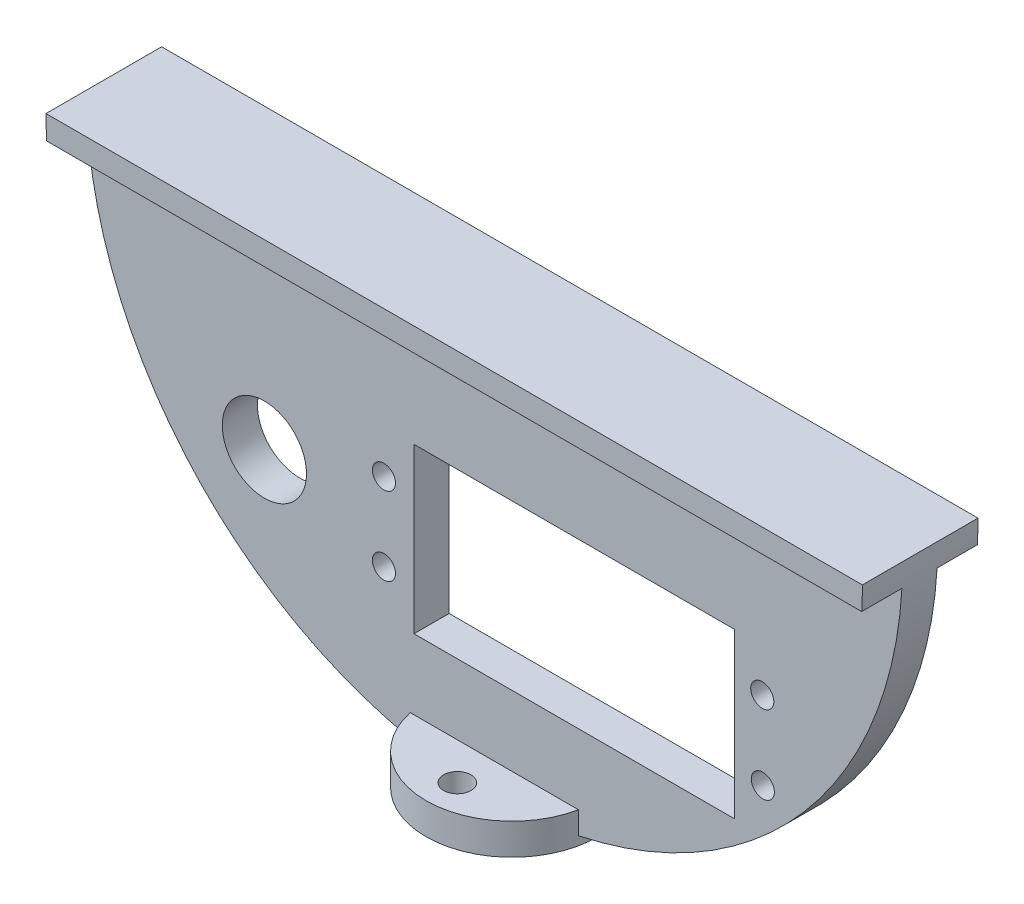
SolidWorks part; units mm, degrees
other "标注1"
sketch "草图11"
ref_plane "前视基准面" through (0, 0, 0) normal (0, 0, 1) x (1, 0, 0)
ref_plane "上视基准面" through (0, 0, 0) normal (0, 1, 0) x (1, 0, 0)
ref_plane "右视基准面" through (0, 0, 0) normal (1, 0, 0) x (0, 0, -1)
sketch "草图1" plane through (0, 0, 0) normal (0, 0, 1) x (1, 0, 0)
  line L0 (-52.25, 0) -> (52.25, 0)
  arc A0 (-52.25, 0) -> (52.25, 0) centre (0, 0) ccw
  dimension "D1" = 52.25
extrude "凸台-拉伸1" add sketch "草图1" along normal blind 4.5
ref_plane "基准面1" through (0, 0, 2.25) normal (0, 0, 1) x (1, 0, 0)
sketch "草图2" plane through (0, 0, 2.25) normal (0, 0, 1) x (1, 0, 0)
  line L1 (-52.25, 0) -> (52.25, 0)
  line L3 (-52.1638, -3) -> (52.1638, -3)
  arc A0 (-52.25, 0) -> (52.25, 0) centre (0, 0) ccw construction
  arc A1 (-52.25, 0) -> (-52.1638, -3) centre (0, 0) ccw
  arc A2 (52.1638, -3) -> (52.25, 0) centre (0, 0) ccw
  dimension "D1" = 3
extrude "凸台-拉伸2" add sketch "草图2" along normal mid plane 14.8
ref_plane "基准面2" through (0, -52.25, 0) normal (0, 1, 0) x (1, 0, 0)
sketch "草图3" plane through (0, -52.25, 0) normal (0, 1, 0) x (1, 0, 0)
  line L0 (-25.9207, -2.25) -> (25.9207, -2.25) construction
  circle A0 centre (0, -2.25) radius 11
  dimension "D1" = 22
extrude "凸台-拉伸3" add sketch "草图3" along normal blind 4
sketch "草图7" plane through (0, -52.25, 0) normal (0, -1, 0) x (1, 0, 0)
  line L0 (25.9207, 2.25) -> (-25.9207, 2.25) construction
  circle A0 centre (0, 9.25) radius 1.75
  circle A1 centre (0, -4.75) radius 1.75
  dimension "D1" = 3.5
  dimension "D2" = 7
  dimension "D3" = 14
extrude "切除-拉伸2" cut sketch "草图7" against normal up to next
sketch "草图10" plane through (0, 0, 4.5) normal (0, 0, 1) x (1, 0, 0)
  line L1 (-10.2939, -18.2668) -> (30.7061, -18.2668)
  line L2 (-10.2939, -18.2668) -> (-10.2939, -39.2668)
  line L3 (-10.2939, -39.2668) -> (30.7061, -39.2668)
  line L4 (30.7061, -18.2668) -> (30.7061, -39.2668)
  circle A0 centre (-14.1439, -23.7668) radius 1.478
  circle A1 centre (34.2861, -23.7668) radius 1.478
  circle A2 centre (-14.1439, -33.7668) radius 1.478
  circle A4 centre (34.3561, -33.7668) radius 1.478
  point P4 (0.0061, -18.2668)
  dimension "D1" = 41
  dimension "D2" = 21
  dimension "D3" = 10.3
  dimension "D4" = 3.85
  dimension "D5" = 5.5
  dimension "D6" = 10
  dimension "D7" = 3.58
  dimension "D8" = 48.5
extrude "切除-拉伸3" cut sketch "草图10" against normal blind 14
sketch "草图12" plane through (0, 0, 4.5) normal (0, 0, 1) x (1, 0, 0)
  circle A1 centre (-29.4454, -28.4254) radius 5.3901
extrude "切除-拉伸4" cut sketch "草图12" against normal blind 15 contours A1
